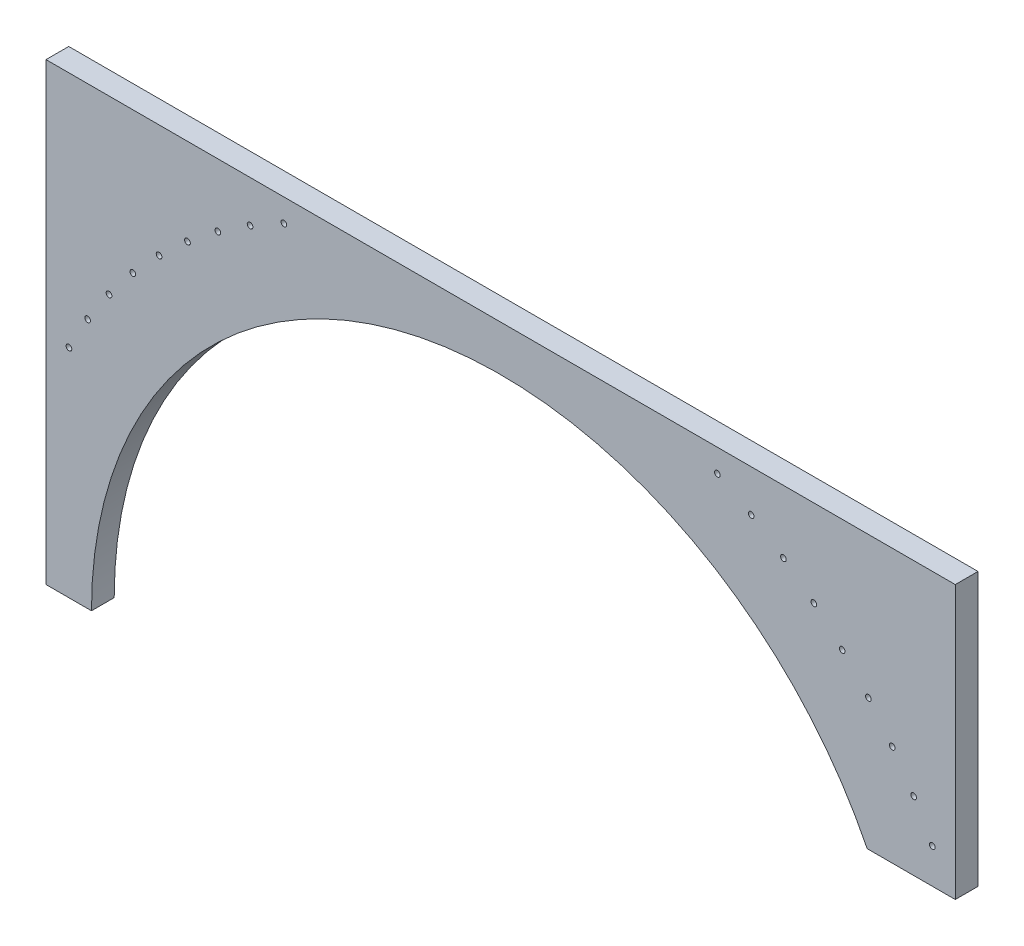
SolidWorks part; units mm, degrees
material "Epoxy, renforcé"
ref_plane "Plan de face" through (0, 0, 0) normal (0, 0, 1) x (1, 0, 0)
ref_plane "Plan de dessus" through (0, 0, 0) normal (0, 1, 0) x (1, 0, 0)
ref_plane "Plan de droite" through (0, 0, 0) normal (1, 0, 0) x (0, 0, -1)
sketch "Esquisse1" plane through (0, 0, 0) normal (0, 0, 1) x (1, 0, 0)
  line L0 (40, 16) -> (40, 40)
  line L1 (40, 40) -> (-40, 40)
  line L2 (-40, 40) -> (-40, 0)
  line L3 (40, 16) -> (32.249, 16)
  line L4 (-36, 0) -> (-40, 0)
  arc A0 (32.249, 16) -> (-36, 0) centre (0, 0) ccw
  dimension "D3" = 36
  dimension "D1" = 80
  dimension "D2" = 24
  dimension "D4" = 40
  dimension "D5" = 40
extrude "Boss.-Extru.1" add sketch "Esquisse1" along normal blind 2
sketch "Esquisse2" plane through (0, 0, 2) normal (0, 0, 1) x (1, 0, 0)
  line L0 (0, 40) -> (0, 0) construction
  line L1 (40, 40) -> (-40, 40) construction
  circle A0 centre (-37.9815, 19.0698) radius 0.25
  circle A1 centre (-36.3355, 22.0449) radius 0.25
  circle A2 centre (-34.4571, 24.8789) radius 0.25
  circle A3 centre (-32.3581, 27.5536) radius 0.25
  circle A4 centre (-30.052, 30.052) radius 0.25
  circle A5 centre (-27.5536, 32.3581) radius 0.25
  circle A6 centre (-24.8789, 34.4571) radius 0.25
  circle A7 centre (-22.0449, 36.3355) radius 0.25
  circle A8 centre (-19.0698, 37.9815) radius 0.25
  circle A9 centre (19.0698, 37.9815) radius 0.25
  circle A10 centre (22.0449, 36.3355) radius 0.25
  circle A11 centre (24.8789, 34.4571) radius 0.25
  circle A12 centre (27.5536, 32.3581) radius 0.25
  circle A13 centre (30.052, 30.052) radius 0.25
  circle A14 centre (32.3581, 27.5536) radius 0.25
  circle A15 centre (34.4571, 24.8789) radius 0.25
  circle A16 centre (36.3355, 22.0449) radius 0.25
  circle A17 centre (37.9815, 19.0698) radius 0.25
extrude "Enlèv. mat.-Extru.1" cut sketch "Esquisse2" against normal blind 2
